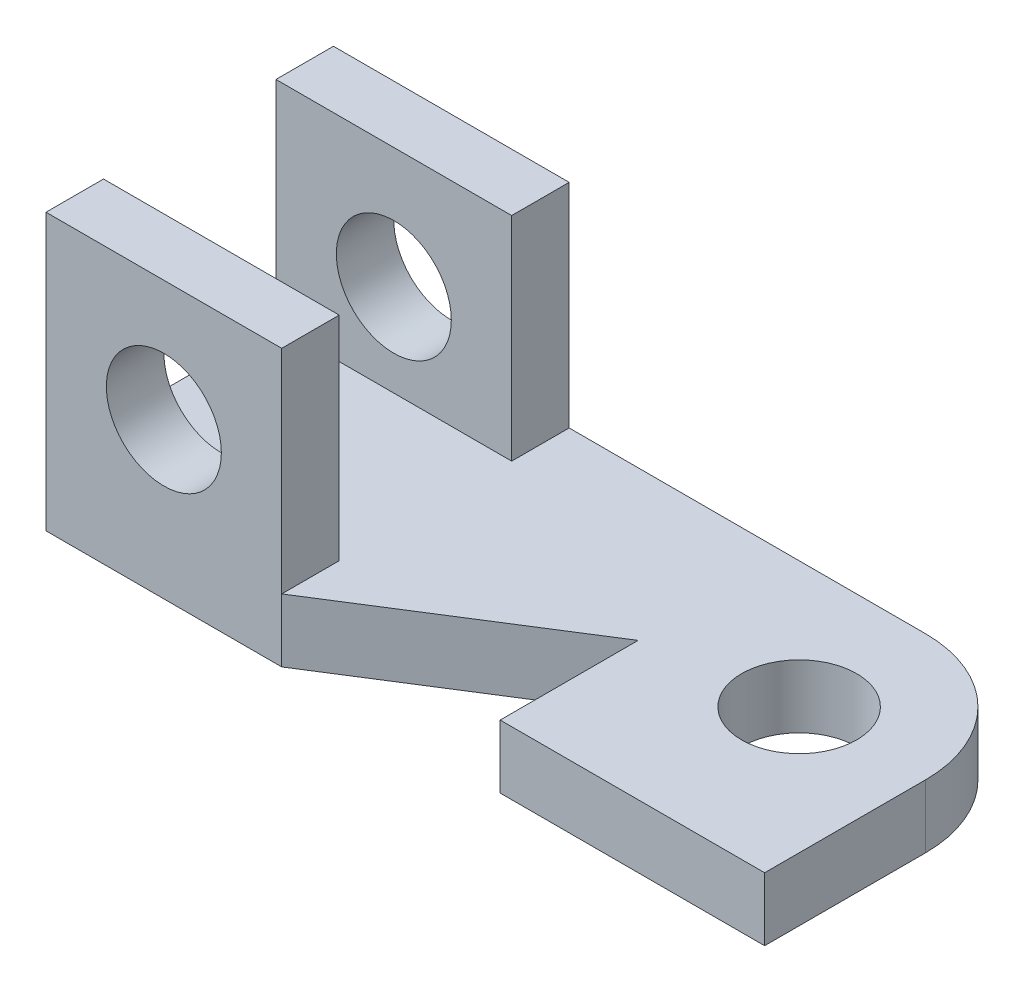
SolidWorks part; units mm, degrees
ref_plane "Front Plane" through (0, 0, 0) normal (0, 0, 1) x (1, 0, 0)
ref_plane "Top Plane" through (0, 0, 0) normal (0, 1, 0) x (1, 0, 0)
ref_plane "Right Plane" through (0, 0, 0) normal (1, 0, 0) x (0, 0, -1)
sketch "Sketch1" plane through (0, 0, 0) normal (0, 1, 0) x (1, 0, 0)
  line L0 (0, 0) -> (1041.4, 0)
  line L1 (1041.4, 0) -> (2006.6, 609.6)
  line L2 (2006.6, 609.6) -> (2006.6, 0)
  line L3 (2006.6, 0) -> (3175, 0)
  line L4 (3175, 0) -> (3175, 711.2)
  line L5 (2616.2, 1270) -> (0, 1270)
  line L6 (0, 1270) -> (0, 0)
  circle A0 centre (2616.2, 711.2) radius 254
  arc A1 (2616.2, 1270) -> (3175, 711.2) centre (2616.2, 711.2) cw
  dimension "D8" = 508
  dimension "D9" = 558.8
  dimension "D1" = 1270
  dimension "D2" = 1041.4
  dimension "D3" = 965.2
  dimension "D4" = 609.6
  dimension "D5" = 1168.4
  dimension "D6" = 558.8
  dimension "D7" = 558.8
extrude "Boss-Extrude1" add sketch "Sketch1" along normal blind 279.4
sketch "Sketch2" plane through (0, 279.4, 0) normal (0, 1, 0) x (1, 0, 0)
  line L0 (0, 1270) -> (0, 0) construction
  line L1 (0, 1270) -> (1041.4, 1270)
  line L2 (0, 1270) -> (0, 1016)
  line L3 (0, 1016) -> (1041.4, 1016)
  line L4 (1041.4, 1270) -> (1041.4, 1016)
  line L5 (0, 254) -> (1041.4, 254)
  line L6 (0, 254) -> (0, 0)
  line L7 (0, 0) -> (1041.4, 0)
  line L8 (1041.4, 254) -> (1041.4, 0)
  line L9 (0, 0) -> (1041.4, 0) construction
  line L10 (2616.2, 1270) -> (0, 1270) construction
  dimension "D1" = 254
  dimension "D2" = 1041.4
  dimension "D3" = 254
  dimension "D4" = 1041.4
extrude "Boss-Extrude2" add sketch "Sketch2" along normal blind 939.8
sketch "Sketch3" plane through (0, 0, 0) normal (0, 0, 1) x (1, 0, 0)
  line L0 (0, 1219.2) -> (0, 0) construction
  line L1 (0, 1219.2) -> (1041.4, 1219.2) construction
  circle A0 centre (520.7, 685.8) radius 254
  dimension "D3" = 508
  dimension "D1" = 520.7
  dimension "D2" = 533.4
extrude "Cut-Extrude1" cut sketch "Sketch3" against normal blind 1270
